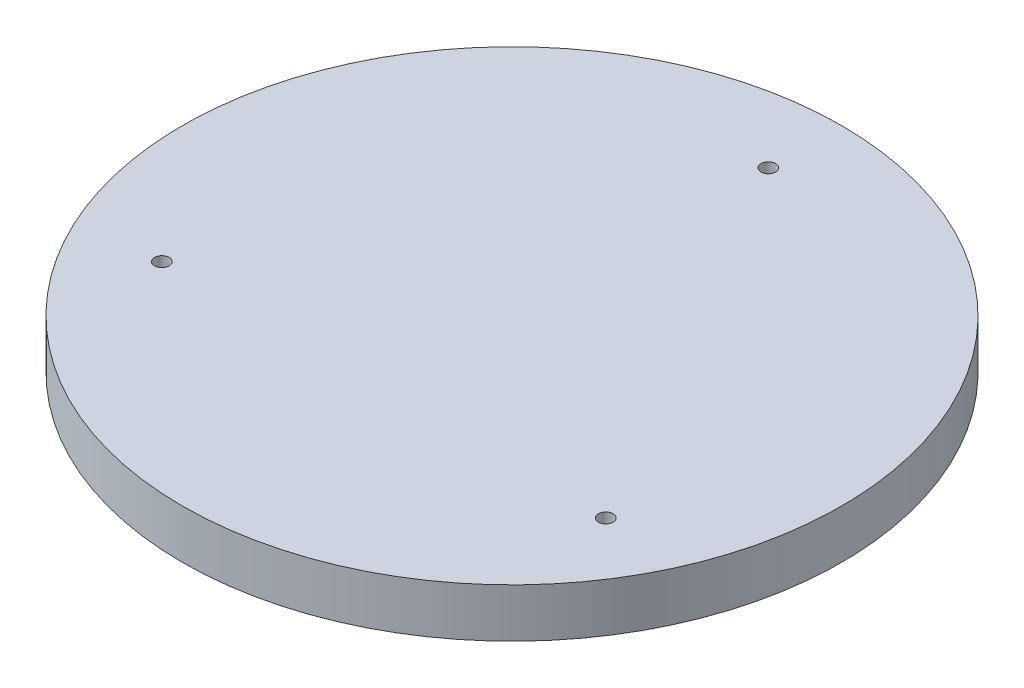
SolidWorks part; units mm, degrees
material "1060 Alloy"
ref_plane "Front Plane" through (0, 0, 0) normal (0, 0, 1) x (1, 0, 0)
ref_plane "Top Plane" through (0, 0, 0) normal (0, 1, 0) x (1, 0, 0)
ref_plane "Right Plane" through (0, 0, 0) normal (1, 0, 0) x (0, 0, -1)
sketch "Sketch1" plane through (0, 0, 0) normal (0, 1, 0) x (1, 0, 0)
  circle A0 centre (0, 0) radius 67.5
  dimension "D1" = 135
extrude "Boss-Extrude1" add sketch "Sketch1" along normal blind 10
sketch "Sketch2" plane through (0, 10, 0) normal (0, 1, 0) x (1, 0, 0)
  line L0 (0, 0) -> (0, 67.5) construction
  line L1 (0, 0) -> (45.4663, -26.25) construction
  line L2 (45.4663, -26.25) -> (58.4567, -33.75) construction
  circle A0 centre (0, 52.5) radius 1.5
  circle A1 centre (0, 0) radius 67.5 construction
  circle A2 centre (45.4663, -26.25) radius 1.5
  circle A3 centre (-45.4663, -26.25) radius 1.5
  dimension "D1" = 3
  dimension "D2" = 15
  dimension "D4" = 120
  dimension "D5" = 15
  dimension "D3" = 3
extrude "Cut-Extrude1" cut sketch "Sketch2" against normal through all
